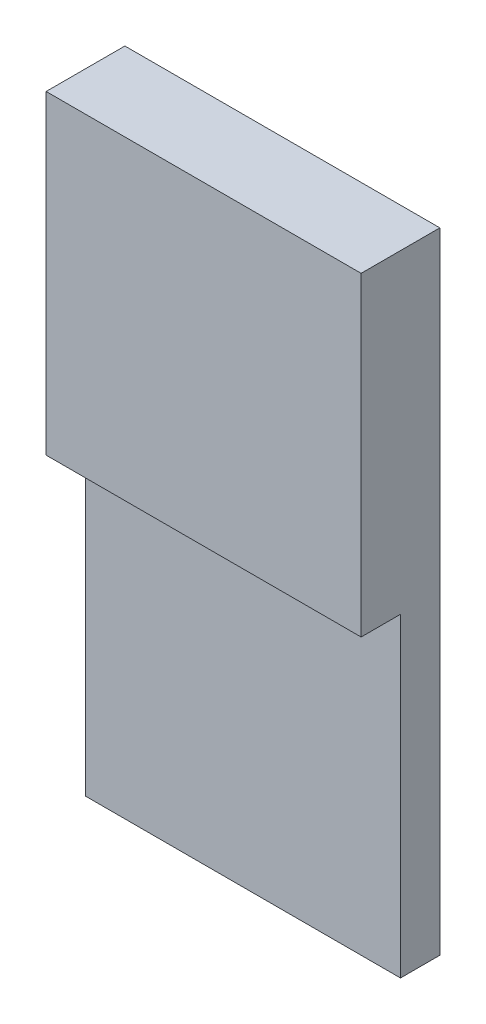
SolidWorks part; units mm, degrees
ref_plane "Front Plane" through (0, 0, 0) normal (0, 0, 1) x (1, 0, 0)
ref_plane "Top Plane" through (0, 0, 0) normal (0, 1, 0) x (1, 0, 0)
ref_plane "Right Plane" through (0, 0, 0) normal (1, 0, 0) x (0, 0, -1)
sketch "Sketch1" plane through (0, 0, 0) normal (0, 0, 1) x (1, 0, 0)
  line L1 (-100, 100) -> (100, 100)
  line L2 (-100, 100) -> (-100, -100)
  line L3 (-100, -100) -> (100, -100)
  line L4 (100, 100) -> (100, -100)
  line L5 (-100, 100) -> (100, -100) construction
  line L6 (-100, -100) -> (100, 100) construction
  point P0 (0, 0)
  dimension "D1" = 200
extrude "Boss-Extrude1" add sketch "Sketch1" along normal blind 25
sketch "Sketch2" plane through (0, 0, 0) normal (0, 0, -1) x (-1, 0, 0)
  line L1 (-100, 100) -> (100, 100)
  line L2 (-100, 100) -> (-100, 300)
  line L3 (-100, 300) -> (100, 300)
  line L4 (100, 100) -> (100, 300)
  dimension "D1" = 200
extrude "Boss-Extrude2" add sketch "Sketch2" against normal blind 50
